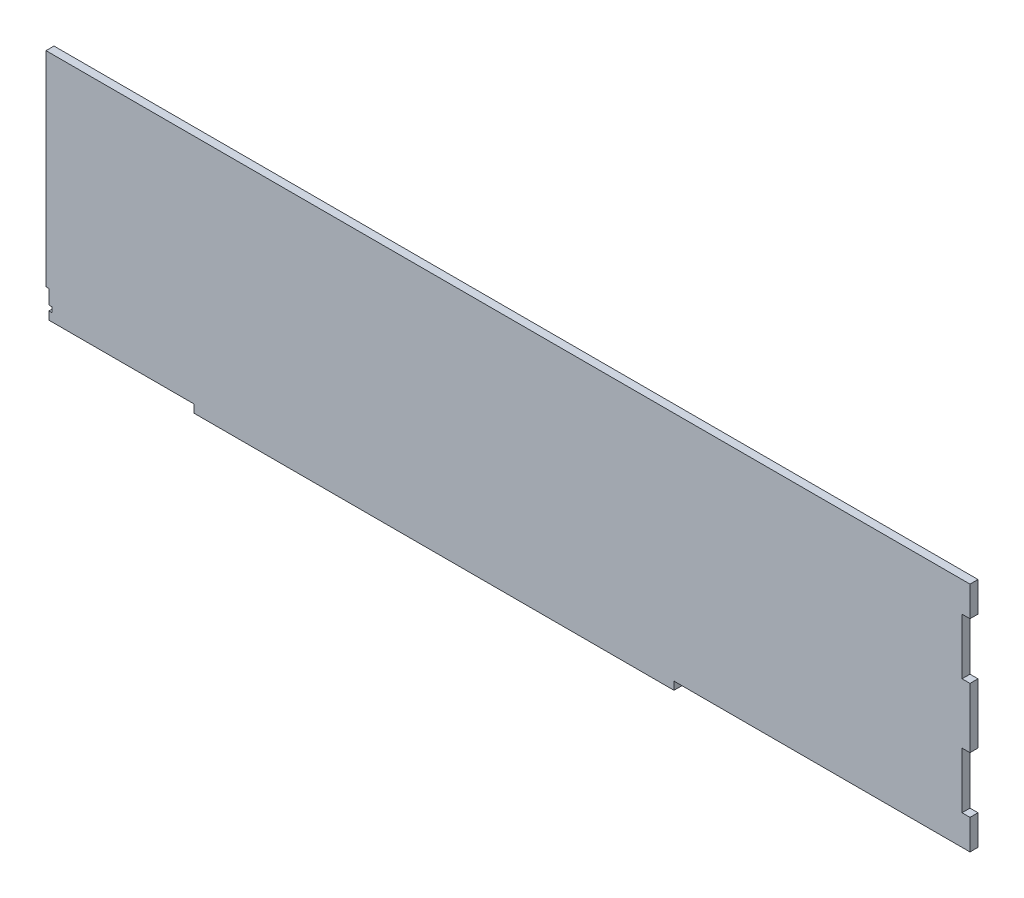
SolidWorks part; units mm, degrees
ref_plane "Alzado" through (0, 0, 0) normal (0, 0, 1) x (1, 0, 0)
ref_plane "Planta" through (0, 0, 0) normal (0, 1, 0) x (1, 0, 0)
ref_plane "Vista lateral" through (0, 0, 0) normal (1, 0, 0) x (0, 0, -1)
sketch "Croquis1" plane through (0, 0, 0) normal (0, 0, 1) x (1, 0, 0)
  line L0 (820, 0) -> (820, -363.7923) construction
  line L1 (0, 0) -> (185, 0)
  line L2 (0, 0) -> (0, 145)
  line L3 (0, 145) -> (1640, 145)
  line L4 (1640, 0) -> (1640, 145)
  line L5 (183.7346, 0) -> (185, 0)
  line L9 (485, -5) -> (185, -5)
  line L11 (670, 0) -> (670, -5)
  line L12 (670, -5) -> (970, -5)
  line L13 (970, 0) -> (970, -5)
  line L15 (1155, 0) -> (1155, -5)
  line L16 (1155, -5) -> (1455, -5)
  line L17 (1455, 0) -> (1455, -5)
  line L18 (185, 0) -> (185, -5)
  line L19 (485, 0) -> (481.1866, 0)
  line L20 (485, 0) -> (485, -5)
  line L21 (481.1866, 0) -> (670, 0)
  line L22 (970, 0) -> (1155, 0)
  line L23 (1455, 0) -> (1640, 0)
  point P15 (820, -5)
  dimension "D1" = 1640
  dimension "D2" = 145
  dimension "D3" = 5
  dimension "D4" = 185
  dimension "D5" = 300
  dimension "D6" = 300
  dimension "D7" = 5
  dimension "D8" = 185
extrude "Saliente-Extruir1" add sketch "Croquis1" along normal blind 5
sketch "Croquis2" plane through (0, 0, 5) normal (0, 0, 1) x (1, 0, 0)
  line L0 (1640, 72.5) -> (1561.7814, 72.5) construction
  line L1 (1640, 0) -> (1640, 145) construction
  line L2 (0, 145) -> (1640, 145) construction
  line L3 (1640, 126.25) -> (1635, 126.25)
  line L4 (1640, 126.25) -> (1640, 91.25)
  line L5 (1640, 91.25) -> (1635, 91.25)
  line L6 (1635, 126.25) -> (1635, 91.25)
  line L7 (1640, 53.75) -> (1635, 53.75)
  line L8 (1635, 18.75) -> (1635, 53.75)
  line L9 (1640, 18.75) -> (1635, 18.75)
  line L10 (1640, 18.75) -> (1640, 53.75)
  line L11 (820, 145) -> (820, 72.5) construction
  line L12 (0, 18.75) -> (0, 53.75)
  line L13 (0, 18.75) -> (5, 18.75)
  line L14 (5, 18.75) -> (5, 53.75)
  line L15 (0, 53.75) -> (5, 53.75)
  line L16 (0, 91.25) -> (5, 91.25)
  line L17 (5, 126.25) -> (5, 91.25)
  line L18 (0, 126.25) -> (5, 126.25)
  line L19 (0, 126.25) -> (0, 91.25)
  dimension "D1" = 35
  dimension "D2" = 18.75
  dimension "D3" = 5
extrude "Cortar-Extruir1" cut sketch "Croquis2" against normal blind 5 contours L7 L8 L9 L10 | L4 L3 L6 L5 | L16 L17 L18 L19 | L12 L15 L14 L13
sketch "Croquis3" plane through (0, 0, 5) normal (0, 0, 1) x (1, 0, 0)
  line L0 (577.5, 0) -> (577.5, 72.6456) construction
  line L1 (485, 0) -> (670, 0) construction
  line L2 (820, -5) -> (820, 72.6456) construction
  line L3 (670, -5) -> (970, -5) construction
  line L4 (579.3, 0) -> (575.7, 0)
  line L5 (575.7, 0) -> (575.7, 5)
  line L6 (575.7, 5) -> (573.9, 5)
  line L7 (573.9, 5) -> (573.9, 8.2)
  line L8 (573.9, 8.2) -> (575.7, 8.2)
  line L9 (575.7, 8.2) -> (575.7, 17.2)
  line L10 (575.7, 17.2) -> (579.3, 17.2)
  line L11 (579.3, 8.2) -> (579.3, 17.2)
  line L12 (581.1, 8.2) -> (579.3, 8.2)
  line L13 (581.1, 5) -> (581.1, 8.2)
  line L14 (579.3, 5) -> (581.1, 5)
  line L15 (579.3, 0) -> (579.3, 5)
  line L16 (1064.3, 8.2) -> (1064.3, 17.2)
  line L17 (1066.1, 8.2) -> (1064.3, 8.2)
  line L18 (1066.1, 5) -> (1066.1, 8.2)
  line L19 (1064.3, 5) -> (1066.1, 5)
  line L20 (1064.3, 0) -> (1064.3, 5)
  line L21 (1060.7, 0) -> (1064.3, 0)
  line L22 (1060.7, 0) -> (1060.7, 5)
  line L23 (1060.7, 5) -> (1058.9, 5)
  line L24 (1058.9, 5) -> (1058.9, 8.2)
  line L25 (1058.9, 8.2) -> (1060.7, 8.2)
  line L26 (1060.7, 8.2) -> (1060.7, 17.2)
  line L27 (1064.3, 17.2) -> (1060.7, 17.2)
  point P16 (577.5, 17.2)
  dimension "D1" = 1.8
  dimension "D2" = 5
  dimension "D3" = 1.8
  dimension "D4" = 3.2
  dimension "D5" = 1.8
  dimension "D6" = 9
extrude "Cortar-Extruir2" cut sketch "Croquis3" against normal blind 10 contours L10 L11 L12 L13 L14 L15 L4 L5 L6 L7 L8 L9 | L16 L27 L26 L25 L24 L23 L22 L21 L20 L19 L18 L17
sketch "Croquis4" plane through (0, 0, 5) normal (0, 0, 1) x (1, 0, 0)
  line L11 (1062.5, 17.2) -> (1062.5, 145)
  line L12 (1064.3, 17.2) -> (1060.7, 17.2) construction
  line L13 (1062.5, 17.2) -> (1062.5, -10.5561)
  line L14 (1062.5, -10.5561) -> (0, -10.5561)
  line L15 (0, -10.5561) -> (0, 145)
  line L16 (0, 145) -> (1062.5, 145)
extrude "Cortar-Extruir5" cut sketch "Croquis4" against normal blind 10
